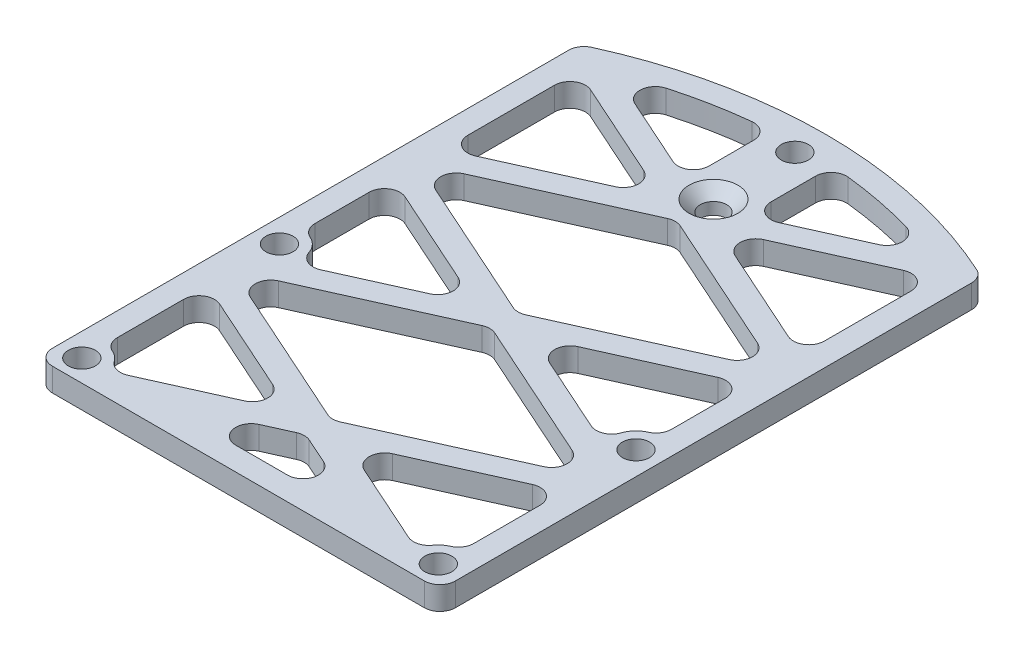
SolidWorks part; units mm, degrees
ref_plane "Front Plane" through (0, 0, 0) normal (0, 0, 1) x (1, 0, 0)
ref_plane "Top Plane" through (0, 0, 0) normal (0, 1, 0) x (1, 0, 0)
ref_plane "Right Plane" through (0, 0, 0) normal (1, 0, 0) x (0, 0, -1)
sketch "Sketch1" plane through (0, 0, 0) normal (0, 1, 0) x (1, 0, 0)
  line L0 (0, 0) -> (0, 35336.2249) construction
  line L1 (-26, -15.8) -> (26, -15.8)
  line L2 (26, -15.8) -> (26, 54.074)
  line L3 (-26, -15.8) -> (-26, 54.074)
  arc A0 (-26, 54.074) -> (26, 54.074) centre (0, 0) cw
  circle A1 centre (-23, -13) radius 2.8 construction
  dimension "D1" = 60
  dimension "D2" = 52
extrude "Boss-Extrude1" add sketch "Sketch1" along normal blind 3
sketch "Sketch2" plane through (0, 3, 0) normal (0, 1, 0) x (1, 0, 0)
  circle A0 centre (-23, -13) radius 1.75
  circle A1 centre (-23, 12.5) radius 1.75
  circle A2 centre (23, -13) radius 1.75
  circle A3 centre (23, 12.5) radius 1.75
  circle A4 centre (-23, 12.5) radius 1.5 construction
  circle A5 centre (-23, -13) radius 1.5 construction
  dimension "D1" = 3.5
extrude "Cut-Extrude1" cut sketch "Sketch2" against normal through all
sketch "Sketch3" plane through (0, 3, 0) normal (0, 1, 0) x (1, 0, 0)
  line L0 (0, 0) -> (0, 50000) construction
  line L1 (-11.1925, 60) -> (49988.8075, 60) construction
  circle A0 centre (0, 56) radius 1.75
  arc A1 (26, 54.074) -> (-26, 54.074) centre (0, 0) ccw construction
  dimension "D1" = 3.5
  dimension "D2" = 4
extrude "Cut-Extrude2" cut sketch "Sketch3" against normal through all
sketch "Sketch4" plane through (0, 3, 0) normal (0, 1, 0) x (1, 0, 0)
  line L0 (-4, 56.8595) -> (-4, 45.8358)
  line L1 (-4, 45.8358) -> (-20.4348, 53.2111)
  line L2 (4, 56.8595) -> (4, 45.8358)
  line L3 (-26, 54.074) -> (-26, -15.8) construction
  line L4 (-23, 51.074) -> (-3.6637, 42.3966)
  line L5 (-3.6637, 42.3966) -> (-23, 33.7192)
  line L6 (-23, 33.7192) -> (-23, 51.074)
  line L7 (3.6637, 42.3966) -> (23, 51.074)
  line L8 (23, 51.074) -> (23, 33.7192)
  line L9 (23, 33.7192) -> (3.6637, 42.3966)
  line L10 (0, 40.7525) -> (-23, 30.431)
  line L11 (-23, 30.431) -> (0, 20.1095)
  line L12 (0, 20.1095) -> (23, 30.431)
  line L13 (23, 30.431) -> (0, 40.7525)
  line L14 (-23, 27.1428) -> (-3.6637, 18.4654)
  line L15 (-3.6637, 18.4654) -> (-20.4392, 10.9371)
  line L16 (-23, 27.1428) -> (-23, 15.5)
  line L17 (3.6637, 18.4654) -> (23, 27.1428)
  line L18 (23, 27.1428) -> (23, 15.5)
  line L19 (3.6637, 18.4654) -> (20.4392, 10.9371)
  line L20 (0, 16.8213) -> (-23, 6.4997)
  line L21 (-23, 6.4997) -> (0, -3.8218)
  line L22 (0, -3.8218) -> (23, 6.4997)
  line L23 (23, 6.4997) -> (0, 16.8213)
  line L24 (23, 3.2115) -> (3.6637, -5.4659)
  line L25 (4, 45.8358) -> (20.4348, 53.2111)
  line L26 (23, 3.2115) -> (23, -10)
  line L27 (-23, -10) -> (-23, 3.2115)
  line L28 (-23, 3.2115) -> (-3.6637, -5.4659)
  line L30 (0, 0) -> (0, 50000) construction
  line L31 (-23, 31.4837) -> (-23, -49968.5163) construction
  line L32 (23, 36.6916) -> (23, -49963.3084) construction
  line L33 (-8.1788, 60) -> (49991.8212, 60) construction
  line L34 (-30.8109, 42.3966) -> (49969.1891, 42.3966) construction
  line L35 (-39.1584, 30.431) -> (49960.8416, 30.431) construction
  line L36 (-34.4581, 18.4654) -> (49965.5419, 18.4654) construction
  line L37 (-35.2038, 6.4997) -> (49964.7962, 6.4997) construction
  line L38 (-33.2543, -12.8) -> (49966.7457, -12.8) construction
  line L40 (-3.6637, -5.4659) -> (-20.0067, -12.8)
  line L41 (3.6637, -5.4659) -> (20.0067, -12.8)
  line L42 (-26, -15.8) -> (26, -15.8) construction
  line L43 (-12.6793, -12.8) -> (0, -7.11)
  line L44 (0, -7.11) -> (12.6793, -12.8)
  line L45 (12.6793, -12.8) -> (-12.6793, -12.8)
  arc A0 (26, 54.074) -> (-26, 54.074) centre (0, 0) ccw construction
  arc A1 (-23, 15.5) -> (-20.4392, 10.9371) centre (-23, 12.5) cw
  arc A2 (23, 15.5) -> (20.4392, 10.9371) centre (23, 12.5) ccw
  arc A3 (23, -10) -> (20.0067, -12.8) centre (23, -13) ccw
  arc A4 (-23, -10) -> (-20.0067, -12.8) centre (-23, -13) cw
  arc A5 (-4, 56.8595) -> (-20.4348, 53.2111) centre (0, 0) ccw
  arc A6 (4, 56.8595) -> (20.4348, 53.2111) centre (0, 0) cw
  dimension "D5" = 3
  dimension "D8" = 3
  dimension "D3" = 3
  dimension "D1" = 3
  dimension "D2" = 3
  dimension "D4" = 3
  dimension "D6" = 3
  dimension "D7" = 3
  dimension "D9" = 8
extrude "Cut-Extrude3" cut sketch "Sketch4" against normal through all
fillet "Fillet1" radius 2 43 edges at (-23, 1.5, -6.4997) (-3.6637, 1.5, 5.4659) (-3.6637, 1.5, -18.4654) (-3.6637, 1.5, -42.3966) (3.6637, 1.5, -42.3966) (3.6637, 1.5, -18.4654) (3.6637, 1.5, 5.4659) (12.6793, 1.5, 12.8) (23, 1.5, -6.4997) (23, 1.5, -30.431) (-20.0067, 1.5, 12.8) (-20.4392, 1.5, -10.9371) (-23, 1.5, -33.7192) (0, 1.5, -20.1095) (0, 1.5, 3.8218) (-12.6793, 1.5, 12.8) (-23, 1.5, 10) (-23, 1.5, -15.5) (-23, 1.5, -30.431) (-23, 1.5, -3.2115) (-23, 1.5, -27.1428) (23, 1.5, -51.074) (23, 1.5, -27.1428) (23, 1.5, -3.2115) (0, 1.5, 7.11) (0, 1.5, -40.7525) (0, 1.5, -16.8213) (20.0067, 1.5, 12.8) (23, 1.5, 10) (20.4392, 1.5, -10.9371) (23, 1.5, -15.5) (23, 1.5, -33.7192) (-23, 1.5, -51.074) (26, 1.5, 15.8) (26, 1.5, -54.074) (-26, 1.5, -54.074) (-26, 1.5, 15.8) (4, 1.5, -45.8358) (-4, 1.5, -56.8595) (-4, 1.5, -45.8358) (20.4348, 1.5, -53.2111) (4, 1.5, -56.8595) (-20.4348, 1.5, -53.2111)
hole_wizard "CSK for M3 Countersunk Flat Head Screw1" positions "Sketch6" profile "Sketch5" countersink size "M3" standard "ISO" end condition through all
sketch "Sketch6" plane through (0, 3, 0) normal (0, 1, 0) x (1, 0, 0)
  line L0 (0, 0) -> (0, 50000) construction
  line L1 (11.3583, 60) -> (-49988.6417, 60) construction
  arc A0 (24.8276, 54.6223) -> (-24.8276, 54.6223) centre (0, 0) ccw construction
  point P0 (0, 45.5)
  dimension "D1" = 14.5
sketch "Sketch5" plane through (0, 3, -45.5) normal (1, 0, 0) x (0, 0, 1)
  line L0 (0, 0) -> (0, 3)
  line L1 (0, 3) -> (1.7, 3)
  line L2 (1.7, 3) -> (1.7, 1.45)
  line L3 (1.7, 1.45) -> (3.15, 0)
  line L5 (3.15, 0) -> (0, 0)
  line L6 (-1.7, 1.45) -> (-3.15, 0) construction
  line L11 (0, -6.35) -> (0, 107.95) construction
  dimension "Thru Hole Dia." = 3.4
  dimension "Thru Hole Depth" = 3
  dimension "Near C'Sink Dia." = 6.3
  dimension "Near C'Sink Angle" = 90
